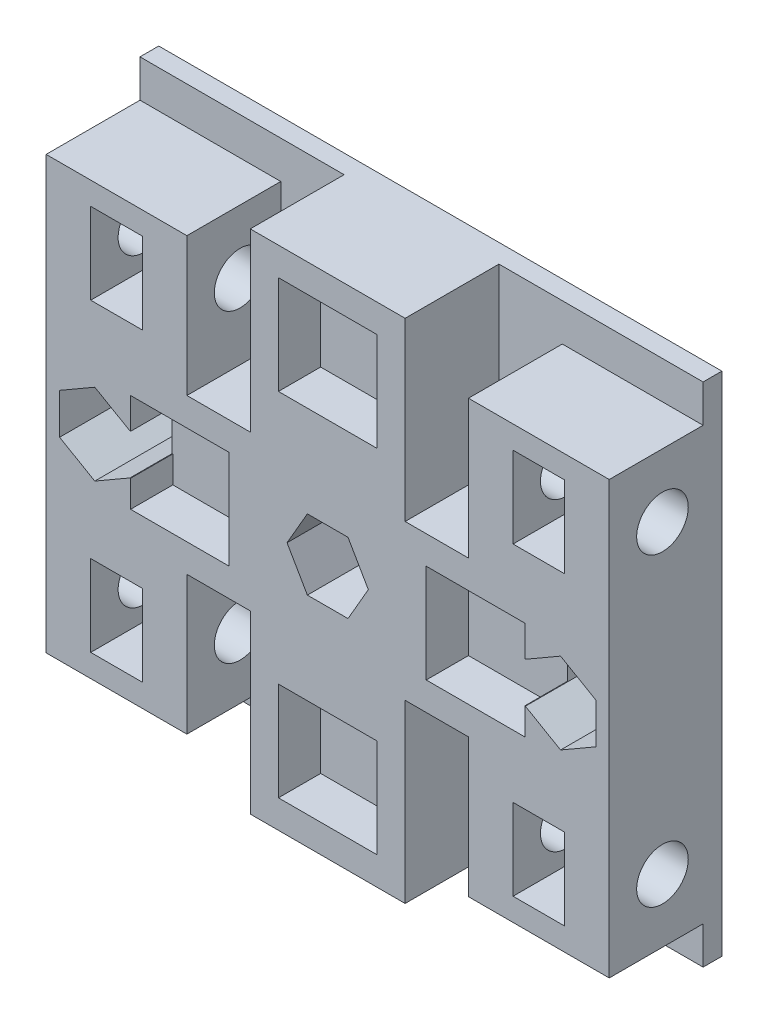
SolidWorks part; units mm, degrees
ref_plane "Plan de face" through (0, 0, 0) normal (0, 0, 1) x (1, 0, 0)
ref_plane "Plan de dessus" through (0, 0, 0) normal (0, 1, 0) x (1, 0, 0)
ref_plane "Plan de droite" through (0, 0, 0) normal (1, 0, 0) x (0, 0, -1)
sketch "Esquisse1" plane through (0, 0, 0) normal (0, 0, 1) x (1, 0, 0)
  line L1 (0, 0) -> (60, 0)
  line L2 (0, 0) -> (0, -54)
  line L3 (0, -54) -> (60, -54)
  line L4 (60, 0) -> (60, -54)
  circle A0 centre (5, -27) radius 2
  circle A1 centre (30, -27) radius 2
  circle A2 centre (55, -27) radius 2
  dimension "D1" = 4
  dimension "D2" = 4
  dimension "D3" = 4
  dimension "D4" = 25
  dimension "D5" = 25
  dimension "D6" = 60
  dimension "D7" = 54
  dimension "D8" = 27
  dimension "D9" = 5
  dimension "D10" = 27
  dimension "D11" = 27
extrude "Boss.-Extru.1" add sketch "Esquisse1" along normal blind 2
sketch "Esquisse2" plane through (0, 0, 2) normal (0, 0, 1) x (1, 0, 0)
  line L0 (0, 0) -> (0, -54) construction
  line L1 (0, -50) -> (15, -50)
  line L2 (15, -50) -> (15, -36.5)
  line L5 (0, -54) -> (60, -54) construction
  line L8 (15, -36.5) -> (0, -36.5)
  dimension "D1" = 4
  dimension "D2" = 15
  dimension "D4" = 13.5
extrude "Boss.-Extru.2" add sketch "Esquisse2" along normal blind 10
sketch "Esquisse4" plane through (0, 0, 0) normal (-1, 0, 0) x (0, 0, 1)
  line L1 (9.5, -45.4151) -> (9.5, -41.0849)
  line L2 (9.5, -41.0849) -> (5.75, -38.9199)
  line L3 (5.75, -38.9199) -> (2, -41.0849)
  line L4 (2, -41.0849) -> (2, -45.4151)
  line L5 (2, -45.4151) -> (5.75, -47.5801)
  line L6 (5.75, -47.5801) -> (9.5, -45.4151)
  line L7 (2, 0) -> (2, -36.5) construction
  line L8 (12, -36.5) -> (2, -36.5) construction
  circle A0 centre (5.75, -43.25) radius 3.75 construction
  dimension "D1" = 7.5
  dimension "D2" = 0
  dimension "D3" = 6.75
extrude "Enlèv. mat.-Extru.2" cut sketch "Esquisse4" against normal blind 16
sketch "Esquisse5" plane through (0, 0, 12) normal (0, 0, 1) x (1, 0, 0)
  line L0 (0, -50) -> (15, -50) construction
  line L1 (0, -36.5) -> (4.75, -36.5)
  line L2 (0, -36.5) -> (0, -50)
  line L3 (0, -50) -> (4.75, -50)
  line L4 (4.75, -36.5) -> (4.75, -50)
  line L5 (15, -36.5) -> (0, -36.5) construction
  line L6 (15, -50) -> (10.25, -50)
  line L7 (15, -50) -> (15, -36.5)
  line L8 (15, -36.5) -> (10.25, -36.5)
  line L9 (10.25, -50) -> (10.25, -36.5)
  dimension "D1" = 4.75
  dimension "D2" = 4.75
  dimension "D3" = 5.5
extrude "Boss.-Extru.3" add sketch "Esquisse5" against normal blind 12
sketch "Esquisse6" plane through (0, 0, 12) normal (0, 0, 1) x (1, 0, 0)
  line L0 (15, -36.5) -> (0, -36.5) construction
  line L1 (4.75, -36.5) -> (10.25, -36.5)
  line L2 (4.75, -36.5) -> (4.75, -50)
  line L3 (4.75, -50) -> (10.25, -50)
  line L4 (10.25, -36.5) -> (10.25, -50)
  line L5 (0, -50) -> (15, -50) construction
  line L6 (0, -36.5) -> (0, -50) construction
  line L7 (15, -50) -> (15, -36.5) construction
  line L9 (4.75, -38.92) -> (10.25, -38.92)
  line L10 (4.75, -38.92) -> (4.75, -47.58)
  line L11 (4.75, -47.58) -> (10.25, -47.58)
  line L12 (10.25, -38.92) -> (10.25, -47.58)
  dimension "D1" = 5.5
  dimension "D2" = 4.75
  dimension "D3" = 4.75
  dimension "D4" = 8.66
  dimension "D5" = 2.42
  dimension "D6" = 2.42
  dimension "D7" = 13.5
extrude "Enlèv. mat.-Extru.3" cut sketch "Esquisse6" against normal blind 6.25 contours L2 L11 L4 L9
sketch "Esquisse7" plane through (0, 0, 0) normal (-1, 0, 0) x (0, 0, 1)
  line L2 (12, -50) -> (2, -50) construction
  line L3 (2, -50) -> (2, -54) construction
  circle A0 centre (6.33, -43.25) radius 2.75
  point P6 (5.3063, -46)
  dimension "D2" = 5.5
  dimension "D1" = 4.33
  dimension "D3" = 6.75
extrude "Enlèv. mat.-Extru.4" cut sketch "Esquisse7" against normal blind 28
ref_plane "Plan2" through (0, -27, 0) normal (0, -1, 0) x (-1, 0, 0)
ref_plane "Plan3" through (30, 0, 0) normal (-1, 0, 0) x (0, 0, 1)
mirror "Symétrie1" about plane through (0, -27, 0) normal (0, -1, 0) of "Enlèv. mat.-Extru.4", "Enlèv. mat.-Extru.3", "Boss.-Extru.3", "Enlèv. mat.-Extru.2", "Boss.-Extru.2"
mirror "Symétrie2" about plane through (30, 0, 0) normal (-1, 0, 0) of "Symétrie1", "Boss.-Extru.2", "Enlèv. mat.-Extru.2", "Boss.-Extru.3", "Enlèv. mat.-Extru.3", "Enlèv. mat.-Extru.4"
sketch "Esquisse8" plane through (0, 0, 2) normal (0, 0, 1) x (1, 0, 0)
  line L0 (0, -54) -> (60, -54) construction
  line L1 (35.25, -54) -> (24.75, -54)
  line L2 (35.25, -54) -> (35.25, -40.5)
  line L3 (35.25, -40.5) -> (24.75, -40.5)
  line L4 (24.75, -54) -> (24.75, -40.5)
  line L5 (35.25, -51) -> (24.75, -51)
  line L6 (38.25, -54) -> (21.75, -54)
  line L7 (38.25, -54) -> (38.25, -37.5)
  line L8 (38.25, -37.5) -> (21.75, -37.5)
  line L9 (21.75, -54) -> (21.75, -37.5)
  line L10 (30, 6.6) -> (30, -6.6) construction
  point P12 (30, -51)
  line M29 (0, -54) -> (60, -54)
  dimension "D1" = 3
  dimension "D2" = 10.5
  dimension "D3" = 10.5
  dimension "D4" = 3
  dimension "D5" = 3
  dimension "D6" = 0
  dimension "D7" = 3
extrude "Boss.-Extru.4" add sketch "Esquisse8" along normal blind 10 contours L9 L4 L3 L2 L7 L8 M29 | L2 L5 L4 M29
sketch "Esquisse12" plane through (0, 0, 2) normal (0, 0, 1) x (1, 0, 0)
  line L1 (15, -36.5) -> (0, -36.5)
  line L2 (15, -36.5) -> (15, -17.5)
  line L3 (15, -17.5) -> (0, -17.5)
  line L4 (0, -36.5) -> (0, -17.5)
extrude "Boss.-Extru.6" add sketch "Esquisse12" along normal blind 10
sketch "Esquisse9" plane through (0, 0, 2) normal (0, 0, 1) x (1, 0, 0)
  line L0 (-6.6, -27) -> (6.6, -27) construction
  line L1 (6, -18.75) -> (22.5, -18.75)
  line L2 (6, -18.75) -> (6, -35.25)
  line L3 (6, -35.25) -> (22.5, -35.25)
  line L4 (22.5, -18.75) -> (22.5, -35.25)
  line L5 (9, -21.75) -> (19.5, -21.75)
  line L6 (9, -21.75) -> (9, -32.25)
  line L7 (9, -32.25) -> (19.5, -32.25)
  line L8 (19.5, -21.75) -> (19.5, -32.25)
  line L10 (0, -4) -> (0, -50) construction
  point P8 (9, -27)
  dimension "D1" = 3
  dimension "D2" = 10.5
  dimension "D3" = 3
  dimension "D4" = 3
  dimension "D5" = 10.5
  dimension "D6" = 3
  dimension "D7" = 0
  dimension "D8" = 9
extrude "Boss.-Extru.7" add sketch "Esquisse9" along normal blind 10
sketch "Esquisse11" plane through (0, 0, 2) normal (0, 0, 1) x (1, 0, 0)
  line L1 (8.9358, -29.3869) -> (8.9358, -25.0568)
  line L2 (8.9358, -25.0568) -> (5.1858, -22.8918)
  line L3 (5.1858, -22.8918) -> (1.4358, -25.0568)
  line L4 (1.4358, -25.0568) -> (1.4358, -29.3869)
  line L5 (1.4358, -29.3869) -> (5.1858, -31.552)
  line L6 (5.1858, -31.552) -> (8.9358, -29.3869)
  line L7 (0, -4) -> (0, -50) construction
  circle A0 centre (5.1858, -27.2219) radius 3.75 construction
  dimension "D1" = 7.5
  dimension "D2" = 1.4358
extrude "Enlèv. mat.-Extru.6" cut sketch "Esquisse11" along normal blind 21
sketch "Esquisse13" plane through (0, 0, 2) normal (0, 0, 1) x (1, 0, 0)
  line L1 (19.5, -32.25) -> (9, -32.25)
  line L2 (19.5, -32.25) -> (19.5, -21.75)
  line L3 (19.5, -21.75) -> (9, -21.75)
  line L4 (9, -32.25) -> (9, -21.75)
  dimension "D1" = 10.5
  dimension "D2" = 10.5
extrude "Enlèv. mat.-Extru.7" cut sketch "Esquisse13" along normal blind 21
mirror "Symétrie3" about plane through (30, 0, 0) normal (-1, 0, 0) of "Boss.-Extru.6", "Enlèv. mat.-Extru.7", "Enlèv. mat.-Extru.6", "Boss.-Extru.7"
mirror "Symétrie4" about plane through (0, -27, 0) normal (0, -1, 0) of "Boss.-Extru.4"
sketch "Esquisse15" plane through (0, 0, 2) normal (0, 0, 1) x (1, 0, 0)
  line L0 (38.25, -37.5) -> (21.75, -37.5) construction
  line L1 (22.5, -37.5) -> (37.5, -37.5)
  line L2 (22.5, -37.5) -> (22.5, -16.5)
  line L3 (22.5, -16.5) -> (37.5, -16.5)
  line L4 (37.5, -37.5) -> (37.5, -16.5)
  line L7 (22.5, -35.25) -> (22.5, -18.75) construction
  line L8 (38.25, -16.5) -> (21.75, -16.5) construction
  line L10 (37.5, -35.25) -> (37.5, -18.75) construction
  line L11 (21.75, -37.5) -> (21.75, -35.25)
  line L12 (15, -35.25) -> (22.5, -35.25) construction
  line L13 (38.25, -37.5) -> (38.25, -35.25)
  line L14 (45, -35.25) -> (37.5, -35.25) construction
  line L15 (38.25, -16.5) -> (38.25, -18.75)
  line L16 (37.5, -18.75) -> (45, -18.75) construction
  line L17 (21.75, -16.5) -> (21.75, -18.75)
  line L18 (22.5, -18.75) -> (15, -18.75) construction
  point P8 (22.5, -27)
  point P9 (30, -16.5)
  point P12 (37.5, -27)
  circle M3 centre (30, -27) radius 2
  line M4 (38.25, -16.5) -> (21.75, -16.5)
  line M10 (15, -18.75) -> (22.5, -18.75)
  line M11 (22.5, -18.75) -> (22.5, -35.25)
  line M12 (22.5, -35.25) -> (15, -35.25)
  line M18 (21.75, -37.5) -> (38.25, -37.5)
  line M24 (45, -35.25) -> (37.5, -35.25)
  line M25 (37.5, -35.25) -> (37.5, -18.75)
  line M26 (37.5, -18.75) -> (45, -18.75)
  dimension "D1" = 0
  dimension "D2" = 0
  dimension "D3" = 0
extrude "Boss.-Extru.9" add sketch "Esquisse15" along normal blind 10 contours L4 L2 M18 M25 M4 M11 M3 | L11 L2 M18 M12 | L13 L4 M18 M24 | L15 L4 M4 M26 | L17 L2 M4 M10
sketch "Esquisse16" plane through (0, 0, 12) normal (0, 0, 1) x (1, 0, 0)
  line L0 (21.75, 0) -> (38.25, 0) construction
  line L1 (32.1651, -23.25) -> (27.8349, -23.25)
  line L2 (27.8349, -23.25) -> (25.6699, -27)
  line L3 (25.6699, -27) -> (27.8349, -30.75)
  line L4 (27.8349, -30.75) -> (32.1651, -30.75)
  line L5 (32.1651, -30.75) -> (34.3301, -27)
  line L6 (34.3301, -27) -> (32.1651, -23.25)
  circle A0 centre (30, -27) radius 3.75 construction
  dimension "D1" = 7.5
  dimension "D2" = 0
extrude "Enlèv. mat.-Extru.8" cut sketch "Esquisse16" against normal blind 10
sketch "Esquisse17" plane through (0, 0, 2) normal (0, 0, 1) x (1, 0, 0)
  line L1 (9, -21.75) -> (19.5, -21.75)
  line L2 (9, -21.75) -> (9, -32.25)
  line L3 (9, -32.25) -> (19.5, -32.25)
  line L4 (19.5, -21.75) -> (19.5, -32.25)
  line L5 (40.5, -21.75) -> (51, -21.75)
  line L6 (40.5, -21.75) -> (40.5, -32.25)
  line L7 (40.5, -32.25) -> (51, -32.25)
  line L8 (51, -21.75) -> (51, -32.25)
  line L9 (24.75, -3) -> (35.25, -3)
  line L10 (24.75, -3) -> (24.75, -13.5)
  line L11 (24.75, -13.5) -> (35.25, -13.5)
  line L12 (35.25, -3) -> (35.25, -13.5)
  line L13 (24.75, -40.5) -> (35.25, -40.5)
  line L14 (24.75, -40.5) -> (24.75, -51)
  line L15 (24.75, -51) -> (35.25, -51)
  line L16 (35.25, -40.5) -> (35.25, -51)
extrude "Boss.-Extru.10" add sketch "Esquisse17" along normal blind 5.5
sketch "Esquisse18" plane through (9, 0, 0) normal (1, 0, 0) x (0, 0, -1)
  line L0 (-12, -32.25) -> (-12, -21.75) construction
  line L1 (-12, -29.3869) -> (-7.5, -29.3869)
  line L2 (-12, -29.3869) -> (-12, -25.0568)
  line L3 (-12, -25.0568) -> (-7.5, -25.0568)
  line L4 (-7.5, -29.3869) -> (-7.5, -25.0568)
  line L5 (-7.5, -21.75) -> (-7.5, -32.25) construction
  dimension "D1" = 0
  dimension "D2" = 0
extrude "Enlèv. mat.-Extru.9" cut sketch "Esquisse18" against normal blind 1.5
mirror "Symétrie5" about plane through (30, 0, 0) normal (-1, 0, 0) of "Enlèv. mat.-Extru.9"
